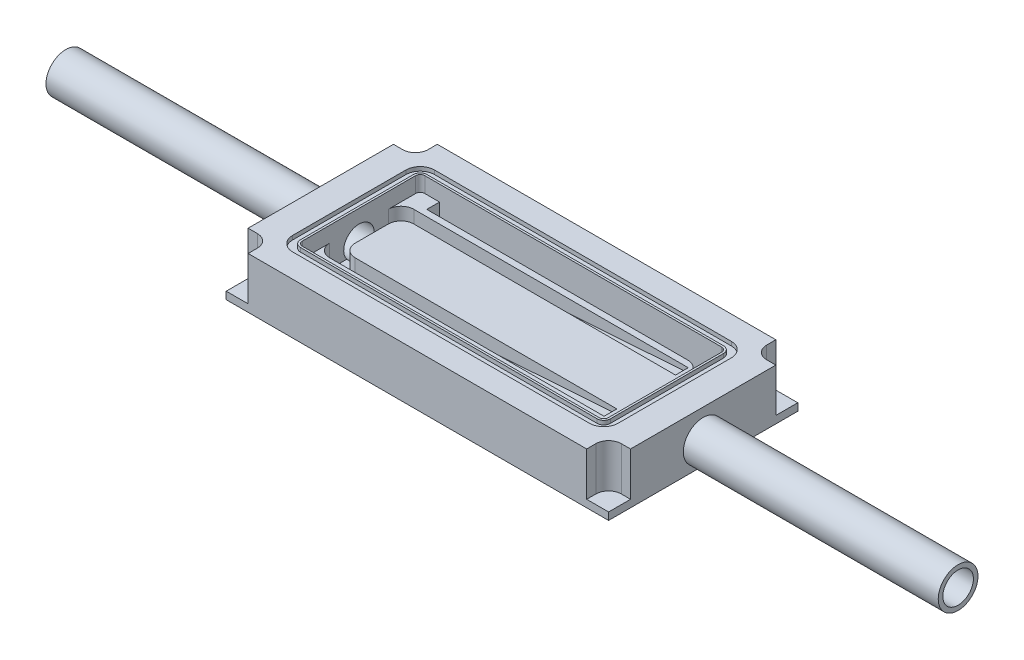
SolidWorks part; units mm, degrees
ref_plane "Front Plane" through (0, 0, 0) normal (0, 0, 1) x (1, 0, 0)
ref_plane "Top Plane" through (0, 0, 0) normal (0, 1, 0) x (1, 0, 0)
ref_plane "Right Plane" through (0, 0, 0) normal (1, 0, 0) x (0, 0, -1)
sketch "Sketch2" plane through (0, 0, 0) normal (0, 1, 0) x (1, 0, 0)
  line L1 (-95.25, -47.117) -> (95.25, -47.117)
  line L2 (-95.25, -47.117) -> (-95.25, 47.117)
  line L3 (-95.25, 47.117) -> (95.25, 47.117)
  line L4 (95.25, -47.117) -> (95.25, 47.117)
  line L5 (-95.25, -47.117) -> (95.25, 47.117) construction
  line L6 (-95.25, 47.117) -> (95.25, -47.117) construction
  point P0 (0, 0)
  dimension "D1" = 94.234
  dimension "D2" = 190.5
extrude "Boss-Extrude1" add sketch "Sketch2" along normal blind 25.4
sketch "Sketch3" plane through (0, 25.4, 0) normal (0, 1, 0) x (1, 0, 0)
  line L1 (-76.2, -30.48) -> (76.2, -30.48)
  line L2 (-76.2, -30.48) -> (-76.2, 30.48)
  line L3 (-76.2, 30.48) -> (76.2, 30.48)
  line L4 (76.2, -30.48) -> (76.2, 30.48)
  line L5 (-76.2, -30.48) -> (76.2, 30.48) construction
  line L6 (-76.2, 30.48) -> (76.2, -30.48) construction
  point P0 (0, 0)
  dimension "D1" = 60.96
  dimension "D2" = 152.4
extrude "Cut-Extrude1" cut sketch "Sketch3" against normal blind 7.7216
fillet "Fillet1" radius 2.286 4 edges at (-76.2, 21.5392, 30.48) (76.2, 21.5392, 30.48) (76.2, 21.5392, -30.48) (-76.2, 21.5392, -30.48)
sketch "Sketch5" plane through (0, 25.4, 0) normal (0, 1, 0) x (1, 0, 0)
  line L0 (-73.914, -35.3441) -> (73.914, -35.3441)
  line L1 (81.0641, -28.194) -> (81.0641, 28.194)
  line L2 (73.914, 35.3441) -> (-73.914, 35.3441)
  line L3 (-81.0641, 28.194) -> (-81.0641, -28.194)
  line L24 (-73.914, -31.496) -> (73.914, -31.496)
  line L25 (77.216, -28.194) -> (77.216, 28.194)
  line L26 (73.914, 31.496) -> (-73.914, 31.496)
  line L27 (-77.216, 28.194) -> (-77.216, -28.194)
  line L28 (-73.914, -31.496) -> (73.914, -31.496)
  line L29 (77.216, -28.194) -> (77.216, 28.194)
  line L30 (73.914, 31.496) -> (-73.914, 31.496)
  line L31 (-77.216, 28.194) -> (-77.216, -28.194)
  arc A0 (73.914, -35.3441) -> (81.0641, -28.194) centre (73.914, -28.194) ccw
  arc A1 (81.0641, 28.194) -> (73.914, 35.3441) centre (73.914, 28.194) ccw
  arc A2 (-73.914, 35.3441) -> (-81.0641, 28.194) centre (-73.914, 28.194) ccw
  arc A3 (-81.0641, -28.194) -> (-73.914, -35.3441) centre (-73.914, -28.194) ccw
  arc A20 (-77.216, -28.194) -> (-73.914, -31.496) centre (-73.914, -28.194) ccw
  arc A21 (73.914, -31.496) -> (77.216, -28.194) centre (73.914, -28.194) ccw
  arc A22 (77.216, 28.194) -> (73.914, 31.496) centre (73.914, 28.194) ccw
  arc A23 (-73.914, 31.496) -> (-77.216, 28.194) centre (-73.914, 28.194) ccw
  arc A24 (-77.216, -28.194) -> (-73.914, -31.496) centre (-73.914, -28.194) ccw
  arc A25 (73.914, -31.496) -> (77.216, -28.194) centre (73.914, -28.194) ccw
  arc A26 (77.216, 28.194) -> (73.914, 31.496) centre (73.914, 28.194) ccw
  arc A27 (-73.914, 31.496) -> (-77.216, 28.194) centre (-73.914, 28.194) ccw
  dimension "D1" = 1.016
  dimension "D2" = 3.8481
extrude "Cut-Extrude2" cut sketch "Sketch5" against normal blind 1.9939
sketch "Sketch6" plane through (0, 25.4, 0) normal (0, 1, 0) x (1, 0, 0)
  line L0 (-84.328, 47.117) -> (-84.328, 42.545)
  line L1 (95.25, 47.117) -> (-95.25, 47.117) construction
  line L2 (-90.678, 36.195) -> (-95.25, 36.195)
  line L3 (-95.25, 47.117) -> (-95.25, -47.117) construction
  line L4 (-84.328, 47.117) -> (-95.25, 47.117)
  line L5 (-95.25, 47.117) -> (-95.25, 36.195)
  arc A0 (-90.678, 36.195) -> (-84.328, 42.545) centre (-90.678, 42.545) ccw
  point P9 (-84.328, 36.195)
  dimension "D3" = 6.35
  dimension "D1" = 10.922
  dimension "D2" = 10.922
extrude "Cut-Extrude3" cut sketch "Sketch6" against normal blind 21.717
mirror "Mirror1" about plane through (0, 0, 0) normal (1, 0, 0) of "Cut-Extrude3" second plane through (0, 0, 0) second plane normal (0, 0, 1)
sketch "Sketch7" plane through (0, 17.6784, 0) normal (0, 1, 0) x (1, 0, 0)
  line L0 (0, 0) -> (64.008, 0) construction
  line L1 (64.008, 0) -> (64.008, 23.9251) construction
  dimension "D1" = 64.008
sketch "Sketch8" plane through (5.1245, 17.6784, 0) normal (0, 1, 0) x (0, 0, -1)
sketch "Sketch13" plane through (0, 17.6784, 0) normal (0, 1, 0) x (1, 0, 0)
  line L0 (76.2, 0) -> (-228.6, 0) construction
  line L1 (76.2, 30.48) -> (76.2, -30.48) construction
  line L3 (73.914, 30.48) -> (-73.914, 30.48) construction
  line L4 (63.5, 24.13) -> (-63, 24.13)
  line L5 (69.85, 30.48) -> (-63, 30.48)
  line L6 (73.914, 30.48) -> (-73.914, 30.48) construction
  line L10 (76.2, -28.194) -> (76.2, 28.194) construction
  line L11 (76.2, 24.13) -> (76.2, -24.13)
  line L13 (69.85, 17.78) -> (69.85, -17.78)
  line L14 (76.2, -28.194) -> (76.2, 28.194) construction
  line L15 (69.85, -30.48) -> (-63, -30.48)
  line L16 (63.5, -24.13) -> (-63, -24.13)
  line L17 (-73.914, -30.48) -> (73.914, -30.48) construction
  line L18 (-76.2, -14.605) -> (-76.2, 14.605)
  line L19 (-76.2, 28.194) -> (-76.2, -28.194) construction
  line L20 (-69.85, -8.255) -> (-69.85, 8.255)
  line L21 (-69.85, 20.955) -> (63, 20.955)
  line L22 (63, 14.605) -> (-63.5, 14.605)
  line L23 (63, -14.605) -> (-63.5, -14.605)
  line L24 (-69.85, -20.955) -> (63, -20.955)
  line L25 (-63, 27.305) -> (-76.2, 27.305) construction
  line L26 (-76.2, 28.194) -> (-76.2, -28.194) construction
  line L27 (63, -17.78) -> (76.2, -17.78) construction
  line L28 (76.2, -28.194) -> (76.2, 28.194) construction
  line L29 (-63, 30.48) -> (-66.5804, 30.48)
  line L30 (-66.5804, 30.48) -> (-66.5804, 24.13)
  line L31 (-66.5804, 24.13) -> (-63, 24.13)
  line L32 (63, 20.955) -> (66.8483, 20.955)
  line L33 (66.8483, 20.955) -> (66.8483, 14.605)
  line L34 (66.8483, 14.605) -> (63, 14.605)
  line L35 (-61.5, 20.955) -> (-64.5, 20.955) construction
  line L37 (-63, -30.48) -> (-66.5804, -30.48)
  line L38 (-66.5804, -30.48) -> (-66.5804, -24.13)
  line L39 (-66.5804, -24.13) -> (-63, -24.13)
  line L40 (63, -20.955) -> (66.8483, -20.955)
  line L41 (66.8483, -20.955) -> (66.8483, -14.605)
  line L42 (66.8483, -14.605) -> (63, -14.605)
  arc A0 (-63, 30.48) -> (-63, 24.13) centre (-63, 27.305) ccw
  arc A2 (69.85, 30.48) -> (76.2, 24.13) centre (69.85, 24.13) cw
  arc A5 (69.85, 17.78) -> (63.5, 24.13) centre (63.5, 17.78) ccw
  arc A6 (69.85, -17.78) -> (63.5, -24.13) centre (63.5, -17.78) cw
  arc A7 (69.85, -30.48) -> (76.2, -24.13) centre (69.85, -24.13) ccw
  arc A8 (-63, -30.48) -> (-63, -24.13) centre (-63, -27.305) cw
  arc A9 (63, 20.955) -> (63, 14.605) centre (63, 17.78) cw
  arc A10 (-69.85, 8.255) -> (-63.5, 14.605) centre (-63.5, 8.255) cw
  arc A11 (-76.2, 14.605) -> (-69.85, 20.955) centre (-69.85, 14.605) cw
  arc A12 (-76.2, -14.605) -> (-69.85, -20.955) centre (-69.85, -14.605) ccw
  arc A13 (-69.85, -8.255) -> (-63.5, -14.605) centre (-63.5, -8.255) ccw
  arc A14 (63, -20.955) -> (63, -14.605) centre (63, -17.78) ccw
  point P32 (-69.85, 0)
  point P35 (-69.85, 0)
  point P43 (69.85, 0)
  point P49 (-76.2, 20.955)
  point P51 (-69.85, 0)
  point P52 (-76.2, 0)
  line M6 (76.2, -28.194) -> (76.2, 28.194)
  line M11 (73.914, 30.48) -> (-73.914, 30.48)
  line M13 (-76.2, 28.194) -> (-76.2, -28.194)
  line M15 (-73.914, -30.48) -> (73.914, -30.48)
  dimension "D2" = 13.2
  dimension "D3" = 6.35
  dimension "D4" = 6.35
  dimension "D6" = 6.35
  dimension "D1" = 6.35
  dimension "D7" = 6.35
  dimension "D10" = 6.35
  dimension "D5" = 6.35
  dimension "D8" = 3.175
extrude "Cut-Extrude6" cut sketch "Sketch13" against normal blind 11.2253 contours A8 A7 A2 A0 L4 A5 L13 A6 L16 M15 M6 M11 | A0 L30 L31 M11 | L24 A14 L23 A13 L20 A10 L22 A9 L21 A11 A12 M13 | L32 A9 L34 L33 | A14 L40 L41 L42 | A8 L39 L38 M15
sketch "Sketch10" plane through (95.25, 0, 0) normal (1, 0, 0) x (0, 0, -1)
  line L2 (0, 19.2659) -> (0, 0) construction
  line L3 (-47.117, 0) -> (47.117, 0) construction
  line L4 (18.6054, 25.4) -> (18.6054, 0) construction
  line L5 (-36.195, 25.4) -> (36.195, 25.4) construction
  circle A1 centre (0, 10.9965) radius 7.62
  circle A2 centre (0, 10.9965) radius 9.906
  dimension "D1" = 2.286
  dimension "D2" = 15.24
extrude "Boss-Extrude2" add sketch "Sketch10" along normal blind 127
sketch "Sketch12" plane through (0, 0, 0) normal (1, 0, 0) x (0, 0, -1)
  line L0 (0, 0) -> (0, 44.6864)
sketch "Sketch16" plane through (95.25, 0, 0) normal (1, 0, 0) x (0, 0, -1)
  circle A1 centre (0, 10.9965) radius 7.62
  circle A6 centre (0, 10.9965) radius 7.62
  dimension "D1" = 0
extrude "Cut-Extrude9" cut sketch "Sketch16" against normal blind 25.4
mirror "Mirror2" about plane through (0, 0, 0) normal (1, 0, 0) of "Cut-Extrude9", "Boss-Extrude2"
sketch "Sketch17" plane through (0, 0, -20.955) normal (0, 0, 1) x (1, 0, 0)
  line L0 (66.8483, 6.4531) -> (66.8483, 15.4331)
  line L2 (-63.5, 6.4531) -> (-63.5, 17.6784) construction
  line L3 (-63.5, 6.4531) -> (-63.5, 17.6784) construction
  line L4 (66.8483, 17.6784) -> (-69.85, 17.6784)
  line L5 (-69.85, 17.6784) -> (-69.85, 6.4531)
  line L6 (-69.85, 6.4531) -> (66.8483, 6.4531)
  line L7 (66.8483, 6.4531) -> (66.8483, 17.6784)
  line L8 (66.8483, 17.6784) -> (-69.85, 17.6784) construction
  line L9 (-69.85, 17.6784) -> (-69.85, 6.4531) construction
  line L11 (66.8483, 6.4531) -> (66.8483, 17.6784) construction
  line L12 (66.8483, 6.4531) -> (-63.5, 6.4531)
  line L13 (-63.5, 6.4531) -> (66.8483, 15.4331)
  dimension "D2" = 8.98
  dimension "D1" = 0
extrude "Boss-Extrude3" add sketch "Sketch17" along normal up to surface (41.91 mm away) up to face at (-1.5008, 12.0657, 20.955)
equation "\"leg\"=5.51181"
equation "\"InletRampHeight\"= 0.353543"
equation "\"Ramp\"=0.307986"
equation "\"D2@Sketch17\"=\"InletRampHeight\""
